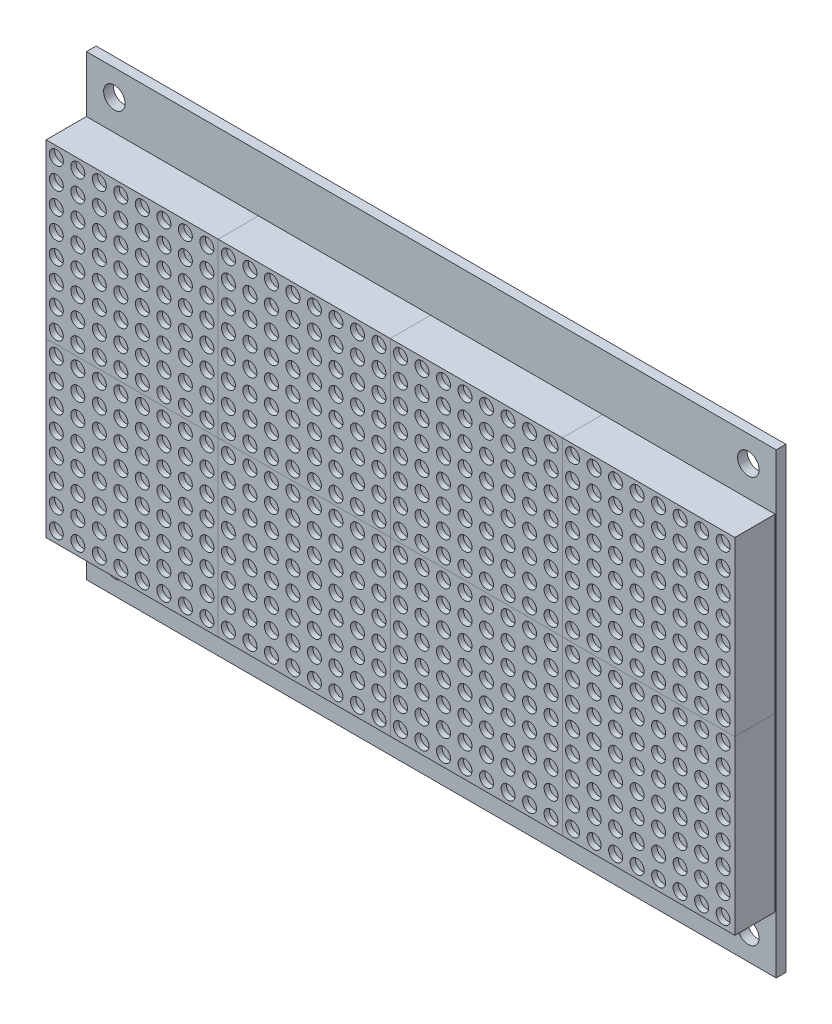
SolidWorks part; units mm, degrees
ref_plane "Front Plane" through (0, 0, 0) normal (0, 0, 1) x (1, 0, 0)
ref_plane "Top Plane" through (0, 0, 0) normal (0, 1, 0) x (1, 0, 0)
ref_plane "Right Plane" through (0, 0, 0) normal (1, 0, 0) x (0, 0, -1)
sketch "Sketch1" plane through (0, 0, 0) normal (0, 0, 1) x (1, 0, 0)
  line L0 (5.2, 80.25) -> (5.2, 85.05) construction
  line L1 (0, 0) -> (128.27, 0)
  line L2 (0, 0) -> (0, 85.05)
  line L3 (0, 85.05) -> (128.27, 85.05)
  line L4 (128.27, 0) -> (128.27, 85.05)
  line L5 (5.2, 80.25) -> (0, 80.25) construction
  line L6 (64.135, 85.05) -> (64.135, 0) construction
  line L7 (0, 42.525) -> (128.27, 42.525) construction
  circle A0 centre (5.2, 80.25) radius 2
  circle A1 centre (123.07, 80.25) radius 2
  circle A2 centre (123.07, 4.8) radius 2
  circle A3 centre (5.2, 4.8) radius 2
  dimension "D3" = 5.2
  dimension "D5" = 4
  dimension "D1" = 128.27
  dimension "D2" = 85.05
  dimension "D4" = 4.8
extrude "Boss-Extrude1" add sketch "Sketch1" along normal blind 1.8
sketch "Sketch2" plane through (0, 0, 1.8) normal (0, 0, 1) x (1, 0, 0)
  line L0 (0, 42.525) -> (128.27, 42.525) construction
  line L1 (0, 85.05) -> (0, 0) construction
  line L2 (128.27, 0) -> (128.27, 85.05) construction
  line L3 (64.135, 85.05) -> (64.135, 0) construction
  line L4 (128.27, 85.05) -> (0, 85.05) construction
  line L5 (0, 0) -> (128.27, 0) construction
  line L6 (64.135, 85.05) -> (0, 85.05) construction
  line L7 (32.0675, 85.05) -> (32.0675, 42.525) construction
  line L9 (0, 42.525) -> (32.0675, 42.525)
  line L10 (0, 42.525) -> (0, 74.5925)
  line L11 (0, 74.5925) -> (32.0675, 74.5925)
  line L12 (32.0675, 42.525) -> (32.0675, 74.5925)
extrude "Boss-Extrude2" add sketch "Sketch2" along normal blind 7.5 separate body
sketch "Sketch3" plane through (0, 0, 9.3) normal (0, 0, 1) x (1, 0, 0)
  line L0 (32.0675, 74.5925) -> (0, 74.5925) construction
  line L1 (0, 74.5925) -> (0, 42.525) construction
  circle A0 centre (1.9, 72.6925) radius 1.3
  circle A1 centre (5.9, 72.675) radius 1.3
  circle A2 centre (9.9, 72.6575) radius 1.3
  circle A3 centre (13.9, 72.64) radius 1.3
  circle A4 centre (17.9, 72.6225) radius 1.3
  circle A5 centre (21.9, 72.605) radius 1.3
  circle A6 centre (25.9, 72.5875) radius 1.3
  circle A7 centre (29.9, 72.57) radius 1.3
  circle A8 centre (1.9, 68.675) radius 1.3
  circle A9 centre (5.9, 68.6575) radius 1.3
  circle A10 centre (9.9, 68.64) radius 1.3
  circle A11 centre (13.9, 68.6225) radius 1.3
  circle A12 centre (17.9, 68.605) radius 1.3
  circle A13 centre (21.9, 68.5875) radius 1.3
  circle A14 centre (25.9, 68.57) radius 1.3
  circle A15 centre (29.9, 68.5525) radius 1.3
  circle A16 centre (1.9, 64.6575) radius 1.3
  circle A17 centre (5.9, 64.64) radius 1.3
  circle A18 centre (9.9, 64.6225) radius 1.3
  circle A19 centre (13.9, 64.605) radius 1.3
  circle A20 centre (17.9, 64.5875) radius 1.3
  circle A21 centre (21.9, 64.57) radius 1.3
  circle A22 centre (25.9, 64.5525) radius 1.3
  circle A23 centre (29.9, 64.535) radius 1.3
  circle A24 centre (1.9, 60.64) radius 1.3
  circle A25 centre (5.9, 60.6225) radius 1.3
  circle A26 centre (9.9, 60.605) radius 1.3
  circle A27 centre (13.9, 60.5875) radius 1.3
  circle A28 centre (17.9, 60.57) radius 1.3
  circle A29 centre (21.9, 60.5525) radius 1.3
  circle A30 centre (25.9, 60.535) radius 1.3
  circle A31 centre (29.9, 60.5175) radius 1.3
  circle A32 centre (1.9, 56.6225) radius 1.3
  circle A33 centre (5.9, 56.605) radius 1.3
  circle A34 centre (9.9, 56.5875) radius 1.3
  circle A35 centre (13.9, 56.57) radius 1.3
  circle A36 centre (17.9, 56.5525) radius 1.3
  circle A37 centre (21.9, 56.535) radius 1.3
  circle A38 centre (25.9, 56.5175) radius 1.3
  circle A39 centre (29.9, 56.5) radius 1.3
  circle A40 centre (1.9, 52.605) radius 1.3
  circle A41 centre (5.9, 52.5875) radius 1.3
  circle A42 centre (9.9, 52.57) radius 1.3
  circle A43 centre (13.9, 52.5525) radius 1.3
  circle A44 centre (17.9, 52.535) radius 1.3
  circle A45 centre (21.9, 52.5175) radius 1.3
  circle A46 centre (25.9, 52.5) radius 1.3
  circle A47 centre (29.9, 52.4825) radius 1.3
  circle A48 centre (1.9, 48.5875) radius 1.3
  circle A49 centre (5.9, 48.57) radius 1.3
  circle A50 centre (9.9, 48.5525) radius 1.3
  circle A51 centre (13.9, 48.535) radius 1.3
  circle A52 centre (17.9, 48.5175) radius 1.3
  circle A53 centre (21.9, 48.5) radius 1.3
  circle A54 centre (25.9, 48.4825) radius 1.3
  circle A55 centre (29.9, 48.465) radius 1.3
  circle A56 centre (1.9, 44.57) radius 1.3
  circle A57 centre (5.9, 44.5525) radius 1.3
  circle A58 centre (9.9, 44.535) radius 1.3
  circle A59 centre (13.9, 44.5175) radius 1.3
  circle A60 centre (17.9, 44.5) radius 1.3
  circle A61 centre (21.9, 44.4825) radius 1.3
  circle A62 centre (25.9, 44.465) radius 1.3
  circle A63 centre (29.9, 44.4475) radius 1.3
  dimension "D1" = 2.6
  dimension "D2" = 1.9
  dimension "D3" = 1.9
  dimension "D4" = 8
  dimension "D5" = 8
extrude "Cut-Extrude1" cut sketch "Sketch3" against normal blind 1
pattern_linear "LPattern2" count 4 spacing 32 along (1, 0, 0) count 2 spacing 32 along (0, -1, 0) of bodies 103
sketch "Sketch4" plane through (0, 0, 0) normal (0, 0, -1) x (-1, 0, 0)
  line L1 (-12, 22.4) -> (-42, 22.4)
  line L2 (-12, 22.4) -> (-12, 31)
  line L3 (-12, 31) -> (-42, 31)
  line L4 (-42, 22.4) -> (-42, 31)
  line L6 (0, 85.05) -> (0, 0) construction
  line L7 (0, 0) -> (-128.27, 0) construction
  dimension "D1" = 42
  dimension "D2" = 31
  dimension "D3" = 8.6
  dimension "D4" = 30
extrude "Boss-Extrude3" add sketch "Sketch4" along normal blind 17
